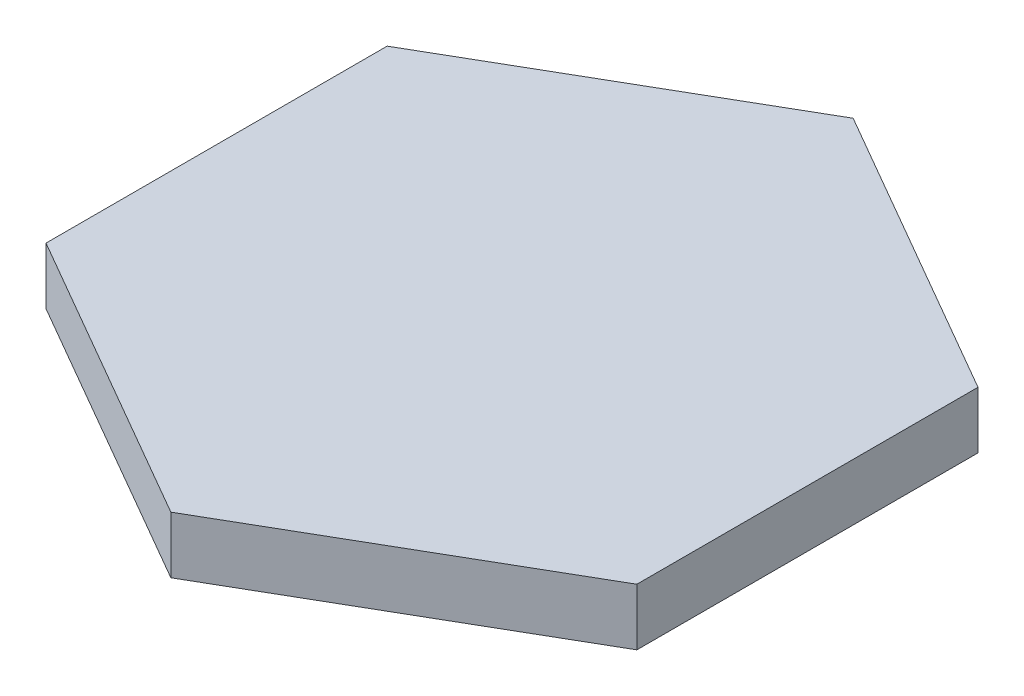
SolidWorks part; units mm, degrees
ref_plane "Front Plane" through (0, 0, 0) normal (0, 0, 1) x (1, 0, 0)
ref_plane "Top Plane" through (0, 0, 0) normal (0, 1, 0) x (1, 0, 0)
ref_plane "Right Plane" through (0, 0, 0) normal (1, 0, 0) x (0, 0, -1)
sketch "Sketch1" plane through (0, 0, 0) normal (0, 1, 0) x (1, 0, 0)
  line L1 (32.9956, 19.05) -> (0, 38.1)
  line L2 (0, 38.1) -> (-32.9956, 19.05)
  line L3 (-32.9956, 19.05) -> (-32.9956, -19.05)
  line L4 (-32.9956, -19.05) -> (0, -38.1)
  line L5 (0, -38.1) -> (32.9956, -19.05)
  line L6 (32.9956, -19.05) -> (32.9956, 19.05)
  line L7 (21.8831, 12.8954) -> (-0.2262, 25.399)
  line L8 (-0.2262, 25.399) -> (-22.1093, 12.5036)
  line L9 (-22.1093, 12.5036) -> (-21.8831, -12.8954)
  line L10 (-21.8831, -12.8954) -> (0.2262, -25.399)
  line L11 (0.2262, -25.399) -> (22.1093, -12.5036)
  line L12 (22.1093, -12.5036) -> (21.8831, 12.8954)
  circle A0 centre (0, 0) radius 32.9956 construction
  circle A1 centre (0, 0) radius 21.997 construction
  point P1 (0, 0)
  point P17 (0, 0)
  dimension "D1" = 38.1
  dimension "D2" = 25.4
  dimension "D3" = 10.8863
  dimension "D4" = 25.399
extrude "Boss-Extrude1" add sketch "Sketch1" against normal blind 6.35 contours L1 L2 L3 L4 L5 L6
